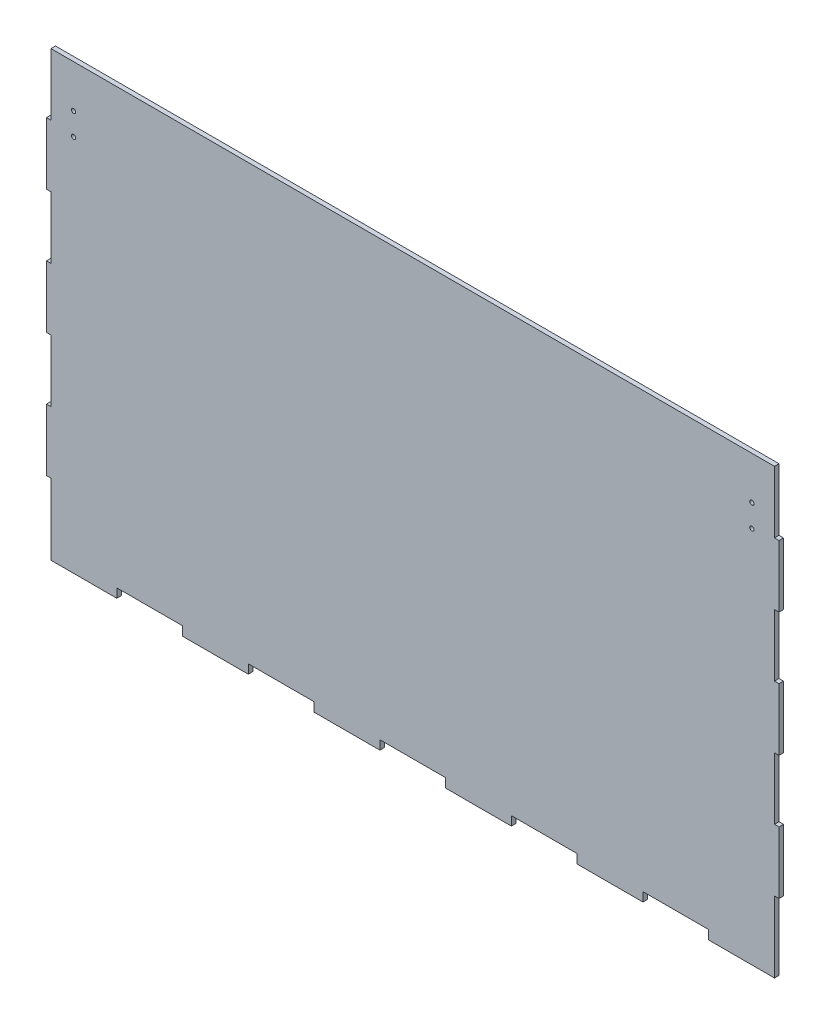
SolidWorks part; units mm, degrees
ref_plane "Front Plane" through (0, 0, 0) normal (0, 0, 1) x (1, 0, 0)
ref_plane "Top Plane" through (0, 0, 0) normal (0, 1, 0) x (1, 0, 0)
ref_plane "Right Plane" through (0, 0, 0) normal (1, 0, 0) x (0, 0, -1)
sketch "Sketch1" plane through (0, 0, 0) normal (0, 0, 1) x (1, 0, 0)
  line L0 (0, 0) -> (508, 0)
  line L1 (508, 0) -> (508, 304.8)
  line L2 (508, 304.8) -> (0, 304.8)
  line L3 (0, 304.8) -> (0, 0)
  line L4 (0, 0) -> (-3.175, 0)
  line L5 (-3.175, 0) -> (-3.175, 43.5429)
  line L6 (-3.175, 43.5429) -> (0, 43.5429)
  line L7 (0, 43.5429) -> (0, 0)
  line L8 (254, 304.8) -> (254, 0) construction
  line L9 (0, 43.5429) -> (-3.175, 43.5429)
  line L10 (-3.175, 43.5429) -> (-3.175, 87.0857)
  line L11 (-3.175, 87.0857) -> (0, 87.0857)
  line L12 (0, 87.0857) -> (0, 43.5429)
  line L13 (0, 87.0857) -> (-3.175, 87.0857)
  line L14 (-3.175, 87.0857) -> (-3.175, 130.6286)
  line L15 (-3.175, 130.6286) -> (0, 130.6286)
  line L16 (0, 130.6286) -> (0, 87.0857)
  line L17 (0, 130.6286) -> (-3.175, 130.6286)
  line L18 (-3.175, 130.6286) -> (-3.175, 174.1714)
  line L19 (-3.175, 174.1714) -> (0, 174.1714)
  line L20 (0, 174.1714) -> (0, 130.6286)
  line L21 (0, 174.1714) -> (-3.175, 174.1714)
  line L22 (-3.175, 174.1714) -> (-3.175, 217.7143)
  line L23 (-3.175, 217.7143) -> (0, 217.7143)
  line L24 (0, 217.7143) -> (0, 174.1714)
  line L25 (0, 217.7143) -> (-3.175, 217.7143)
  line L26 (-3.175, 217.7143) -> (-3.175, 261.2571)
  line L27 (-3.175, 261.2571) -> (0, 261.2571)
  line L28 (0, 261.2571) -> (0, 217.7143)
  line L29 (0, 261.2571) -> (-3.175, 261.2571)
  line L30 (-3.175, 261.2571) -> (-3.175, 304.8)
  line L31 (-3.175, 304.8) -> (0, 304.8)
  line L32 (0, 304.8) -> (0, 261.2571)
  line L33 (0, 0) -> (0, 43.5429) construction
  line L34 (508, 261.2571) -> (508, 217.7143)
  line L35 (511.175, 261.2571) -> (508, 261.2571)
  line L36 (511.175, 217.7143) -> (511.175, 261.2571)
  line L37 (508, 217.7143) -> (511.175, 217.7143)
  line L38 (508, 174.1714) -> (508, 130.6286)
  line L39 (511.175, 174.1714) -> (508, 174.1714)
  line L40 (511.175, 130.6286) -> (511.175, 174.1714)
  line L41 (508, 130.6286) -> (511.175, 130.6286)
  line L42 (508, 87.0857) -> (508, 43.5429)
  line L43 (511.175, 87.0857) -> (508, 87.0857)
  line L44 (511.175, 43.5429) -> (511.175, 87.0857)
  line L45 (508, 43.5429) -> (511.175, 43.5429)
  line L46 (0, 0) -> (0, -6.35)
  line L47 (0, -6.35) -> (46.1818, -6.35)
  line L48 (46.1818, -6.35) -> (46.1818, 0)
  line L49 (46.1818, 0) -> (0, 0)
  line L50 (46.1818, 0) -> (46.1818, -6.35)
  line L51 (46.1818, -6.35) -> (92.3636, -6.35)
  line L52 (92.3636, -6.35) -> (92.3636, 0)
  line L53 (92.3636, 0) -> (46.1818, 0)
  line L54 (92.3636, 0) -> (92.3636, -6.35)
  line L55 (92.3636, -6.35) -> (138.5455, -6.35)
  line L56 (138.5455, -6.35) -> (138.5455, 0)
  line L57 (138.5455, 0) -> (92.3636, 0)
  line L58 (138.5455, 0) -> (138.5455, -6.35)
  line L59 (138.5455, -6.35) -> (184.7273, -6.35)
  line L60 (184.7273, -6.35) -> (184.7273, 0)
  line L61 (184.7273, 0) -> (138.5455, 0)
  line L62 (184.7273, 0) -> (184.7273, -6.35)
  line L63 (184.7273, -6.35) -> (230.9091, -6.35)
  line L64 (230.9091, -6.35) -> (230.9091, 0)
  line L65 (230.9091, 0) -> (184.7273, 0)
  line L66 (230.9091, 0) -> (230.9091, -6.35)
  line L67 (230.9091, -6.35) -> (277.0909, -6.35)
  line L68 (277.0909, -6.35) -> (277.0909, 0)
  line L69 (277.0909, 0) -> (230.9091, 0)
  line L70 (277.0909, 0) -> (277.0909, -6.35)
  line L71 (277.0909, -6.35) -> (323.2727, -6.35)
  line L72 (323.2727, -6.35) -> (323.2727, 0)
  line L73 (323.2727, 0) -> (277.0909, 0)
  line L74 (323.2727, 0) -> (323.2727, -6.35)
  line L75 (323.2727, -6.35) -> (369.4545, -6.35)
  line L76 (369.4545, -6.35) -> (369.4545, 0)
  line L77 (369.4545, 0) -> (323.2727, 0)
  line L78 (369.4545, 0) -> (369.4545, -6.35)
  line L79 (369.4545, -6.35) -> (415.6364, -6.35)
  line L80 (415.6364, -6.35) -> (415.6364, 0)
  line L81 (415.6364, 0) -> (369.4545, 0)
  line L82 (415.6364, 0) -> (415.6364, -6.35)
  line L83 (415.6364, -6.35) -> (461.8182, -6.35)
  line L84 (461.8182, -6.35) -> (461.8182, 0)
  line L85 (461.8182, 0) -> (415.6364, 0)
  line L86 (461.8182, 0) -> (461.8182, -6.35)
  line L87 (461.8182, -6.35) -> (508, -6.35)
  line L88 (508, -6.35) -> (508, 0)
  line L89 (508, 0) -> (461.8182, 0)
  line L90 (0, 0) -> (46.1818, 0) construction
  dimension "D1" = 508
  dimension "D2" = 304.8
  dimension "D3" = 3.175
  dimension "D5" = 43.5429
  dimension "D6" = 43.5429
  dimension "D7" = 6.35
  dimension "D9" = 46.1818
  dimension "D10" = 46.1818
  dimension "D4" = 7
  dimension "D8" = 11
extrude "Boss-Extrude1" add sketch "Sketch1" along normal blind 3.175 contours L2 L3 L0 L1 | L47 L48 L0 L46 | L55 L56 L0 L52 | L63 L64 L0 L60 | L71 L72 L0 L68 | L79 L80 L0 L76 | L87 L88 L0 L84 | L1 L45 L44 L43 | L1 L41 L40 L39 | L1 L37 L36 L35 | L26 L27 L28 L25 | L18 L19 L20 L17 | L10 L11 L12 L9
sketch "Sketch2" plane through (0, 0, 3.175) normal (0, 0, 1) x (1, 0, 0)
  line L0 (254, 304.8) -> (254, 0) construction
  line L1 (508, 304.8) -> (0, 304.8) construction
  line L2 (230.9091, 0) -> (277.0909, 0) construction
  line L4 (-3.175, 217.7143) -> (-3.175, 261.2571) construction
  circle A0 centre (15.875, 274.8) radius 1.5
  circle A1 centre (15.875, 259.05) radius 1.5
  circle A2 centre (492.125, 259.05) radius 1.5
  circle A3 centre (492.125, 274.8) radius 1.5
  point P12 (0, 0)
  dimension "D1" = 3
  dimension "D2" = 3
  dimension "D3" = 15.75
  dimension "D4" = 19.05
  dimension "D5" = 30
extrude "Cut-Extrude1" cut sketch "Sketch2" against normal up to surface (3.175 mm away) up to face at (254, 87.3125, 0)
equation "\"Height\"= 12in"
equation "\"Depth\"= 7in"
equation "\"WallThickness\"= 0.125in"
equation "\"FloorThickness\"= 0.25in"
equation "\"Width\" = 30in"
equation "\"D7@Sketch1\"=\"FloorThickness\""
equation "\"D10@Sketch1\"=\"D1@Sketch1\"/\"D8@Sketch1\""
equation "\"D9@Sketch1\"=\"D10@Sketch1\""
equation "\"D1@Boss-Extrude1\"=\"WallThickness\""
